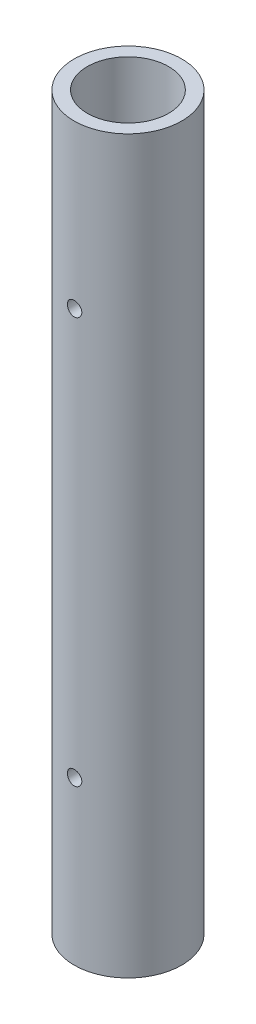
SolidWorks part; units mm, degrees
material "PVC Rigid"
ref_plane "Front Plane" through (0, 0, 0) normal (0, 0, 1) x (1, 0, 0)
ref_plane "Top Plane" through (0, 0, 0) normal (0, 1, 0) x (1, 0, 0)
ref_plane "Right Plane" through (0, 0, 0) normal (1, 0, 0) x (0, 0, -1)
sketch "Sketch1" plane through (0, 0, 0) normal (0, 1, 0) x (1, 0, 0)
  circle A0 centre (0, 0) radius 12.7
  circle A1 centre (0, 0) radius 16.8275
  dimension "D1" = 33.655
  dimension "D2" = 25.4
extrude "Boss-Extrude1" add sketch "Sketch1" along normal blind 228.6
sketch "Sketch2" plane through (0, 0, 0) normal (0, 0, 1) x (1, 0, 0)
  line L0 (0, 228.6) -> (0, 0) construction
  line L1 (12.7, 228.6) -> (-12.7, 228.6) construction
  circle A0 centre (0, 177.8) radius 2.2479
  circle A1 centre (0, 50.8) radius 2.2479
  dimension "D1" = 4.4958
  dimension "D2" = 127
  dimension "D3" = 50.8
extrude "Cut-Extrude1" cut sketch "Sketch2" against normal through all both and the other way through all
